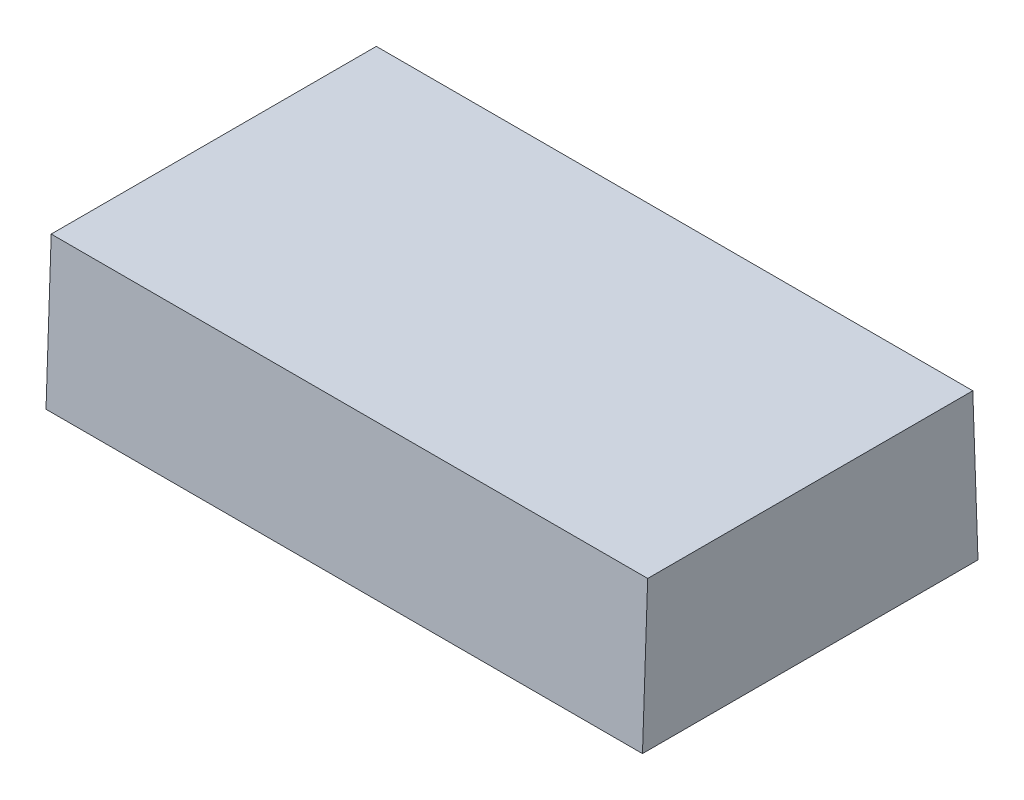
SolidWorks part; units mm, degrees
ref_plane "Front Plane" through (0, 0, 0) normal (0, 0, 1) x (1, 0, 0)
ref_plane "Top Plane" through (0, 0, 0) normal (0, 1, 0) x (1, 0, 0)
ref_plane "Right Plane" through (0, 0, 0) normal (1, 0, 0) x (0, 0, -1)
sketch "Sketch6" plane through (0, 0, 0) normal (1, 0, 0) x (0, 0, -1)
  line L0 (0, 0) -> (114.3, 0)
  line L1 (55, 0) -> (-55, 0) construction
  line L2 (114.3, 0) -> (112.526, 50.8)
  line L3 (112.526, 50.8) -> (1.774, 50.8)
  line L4 (1.774, 50.8) -> (0, 0)
  point P5 (0, 0)
  dimension "D1" = 92
  dimension "D2" = 92
  dimension "D3" = 114.3
  dimension "D5" = 50.8
extrude "Boss-Extrude5" add sketch "Sketch6" along normal blind 203.2
sketch "Sketch9" plane through (0, 0, 0) normal (1, 0, 0) x (0, 0, -1)
  line L0 (103.8477, 9.525) -> (102.7389, 41.275)
  line L1 (102.7389, 41.275) -> (10.9722, 41.275)
  line L2 (10.9722, 41.275) -> (9.8634, 9.525)
  line L3 (9.8634, 9.525) -> (103.8477, 9.525)
  line L5 (0, 0) -> (114.3, 0) construction
  line L9 (112.526, 50.8) -> (1.774, 50.8) construction
  dimension "D1" = 9.525
  dimension "D2" = 9.525
  dimension "D3" = 92
  dimension "D4" = 92
extrude "Cut-Extrude3" cut sketch "Sketch9" along direction (1, 0, 0) on the side of the normal blind 182.88 from offset 9.525 contours L0 L1 L2 L3
